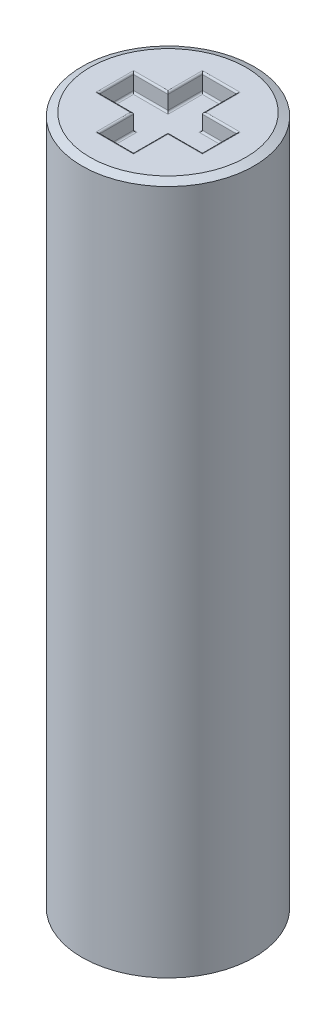
SolidWorks part; units mm, degrees
ref_plane "Front Plane" through (0, 0, 0) normal (0, 0, 1) x (1, 0, 0)
ref_plane "Top Plane" through (0, 0, 0) normal (0, 1, 0) x (1, 0, 0)
ref_plane "Right Plane" through (0, 0, 0) normal (1, 0, 0) x (0, 0, -1)
sketch "Sketch1" plane through (0, 0, 0) normal (0, 1, 0) x (1, 0, 0)
  circle A0 centre (0, 0) radius 2.5
  dimension "D1" = 5
extrude "Boss-Extrude1" add sketch "Sketch1" along normal blind 20
chamfer "Chamfer1" distance 0.1 angle 67 1 edges at (0, 20, 2.5)
sketch "Sketch2" plane through (0, 20, 0) normal (0, 1, 0) x (1, 0, 0)
  line L0 (0.5, 0.5) -> (0.5, 1.5)
  line L1 (0.5, -1.5) -> (-0.5, -1.5)
  line L2 (0.5, -1.5) -> (0.5, -0.5)
  line L3 (0.5, 1.5) -> (-0.5, 1.5)
  line L4 (-0.5, -1.5) -> (-0.5, -0.5)
  line L7 (-1.5, -0.5) -> (-0.5, -0.5)
  line L8 (-1.5, -0.5) -> (-1.5, 0.5)
  line L9 (-1.5, 0.5) -> (-0.5, 0.5)
  line L10 (1.5, -0.5) -> (1.5, 0.5)
  line L15 (0.5, -0.5) -> (1.5, -0.5)
  line L17 (-0.5, 0.5) -> (-0.5, 1.5)
  line L18 (0.5, 0.5) -> (1.5, 0.5)
  point P0 (0, 0)
  point P6 (0, 0)
  dimension "D1" = 1
  dimension "D2" = 1
  dimension "D3" = 3
  dimension "D4" = 3
extrude "Cut-Extrude1" cut sketch "Sketch2" against normal blind 0.5
fillet "Fillet1" radius 0.05 24 edges at (-1, 20, -0.5) (-1.5, 20, 0) (-1, 20, 0.5) (-0.5, 20, 1) (0, 20, 1.5) (0.5, 20, 1) (1, 20, 0.5) (1.5, 20, 0) (1, 20, -0.5) (0.5, 20, -1) (0, 20, -1.5) (-0.5, 20, -1) (0, 19.5, -1.5) (0.5, 19.5, -1) (1, 19.5, -0.5) (1.5, 19.5, 0) (1, 19.5, 0.5) (0.5, 19.5, 1) (0, 19.5, 1.5) (-0.5, 19.5, 1) (-1, 19.5, 0.5) (-1.5, 19.5, 0) (-1, 19.5, -0.5) (-0.5, 19.5, -1)
